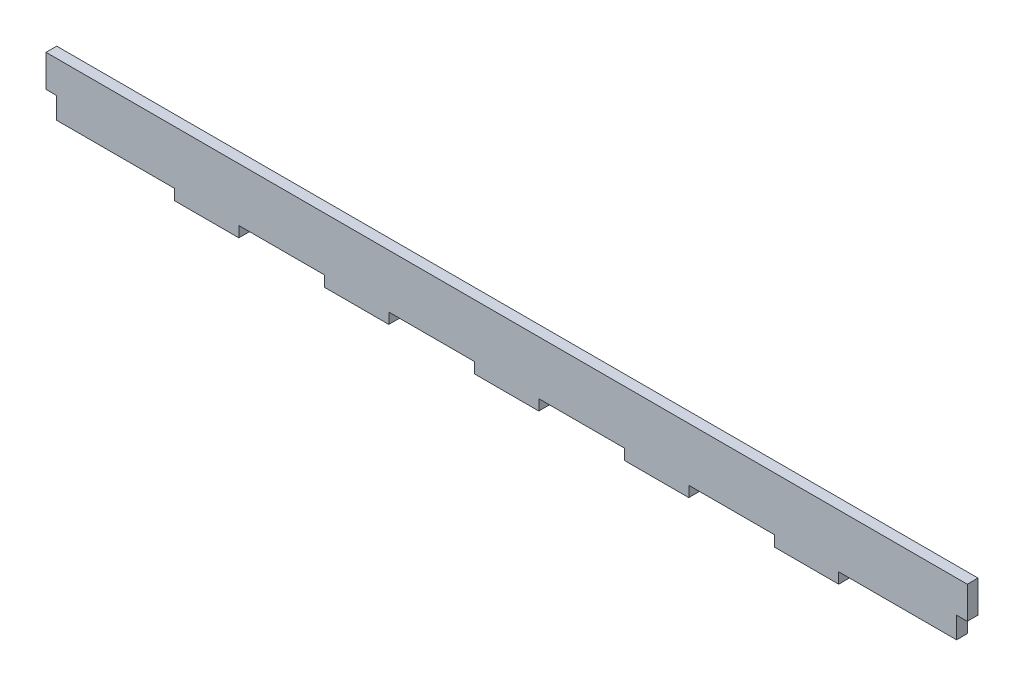
SolidWorks part; units mm, degrees
ref_plane "Front Plane" through (0, 0, 0) normal (0, 0, 1) x (1, 0, 0)
ref_plane "Top Plane" through (0, 0, 0) normal (0, 1, 0) x (1, 0, 0)
ref_plane "Right Plane" through (0, 0, 0) normal (1, 0, 0) x (0, 0, -1)
sketch "Sketch1" plane through (0, 0, 0) normal (0, 0, 1) x (1, 0, 0)
  line L36 (-435, -420) -> (-435, -430)
  line L40 (-440, -405) -> (-440, -420)
  line L41 (-440, -420) -> (-435, -420)
  line L46 (-225, -435) -> (-225, -409.5054) construction
  line L47 (-210, -430) -> (-210, -435)
  line L48 (-170, -430) -> (-210, -430)
  line L49 (-170, -435) -> (-170, -430)
  line L50 (-140, -435) -> (-170, -435)
  line L51 (-140, -430) -> (-140, -435)
  line L52 (-100, -430) -> (-140, -430)
  line L53 (-100, -435) -> (-100, -430)
  line L54 (-70, -435) -> (-100, -435)
  line L55 (-70, -430) -> (-70, -435)
  line L56 (-15, -430) -> (-70, -430)
  line L58 (-440, -405) -> (-10, -405)
  line L59 (-10, -420) -> (-15, -420)
  line L60 (-10, -405) -> (-10, -420)
  line L63 (-15, -420) -> (-15, -430)
  line L71 (-435, -430) -> (-380, -430)
  line L72 (-380, -430) -> (-380, -435)
  line L73 (-380, -435) -> (-350, -435)
  line L74 (-350, -435) -> (-350, -430)
  line L75 (-350, -430) -> (-310, -430)
  line L76 (-310, -430) -> (-310, -435)
  line L77 (-310, -435) -> (-280, -435)
  line L78 (-280, -435) -> (-280, -430)
  line L79 (-280, -430) -> (-240, -430)
  line L80 (-240, -430) -> (-240, -435)
  line L81 (-240, -435) -> (-210, -435)
  point P0 (-440, -405)
  point P18 (-225, -435)
  point P37 (-225, -390)
  dimension "D1" = 25
  dimension "D2" = 10
  dimension "D3" = 15
  dimension "D4" = 5
extrude "Boss-Extrude1" add sketch "Sketch1" along normal blind 5
